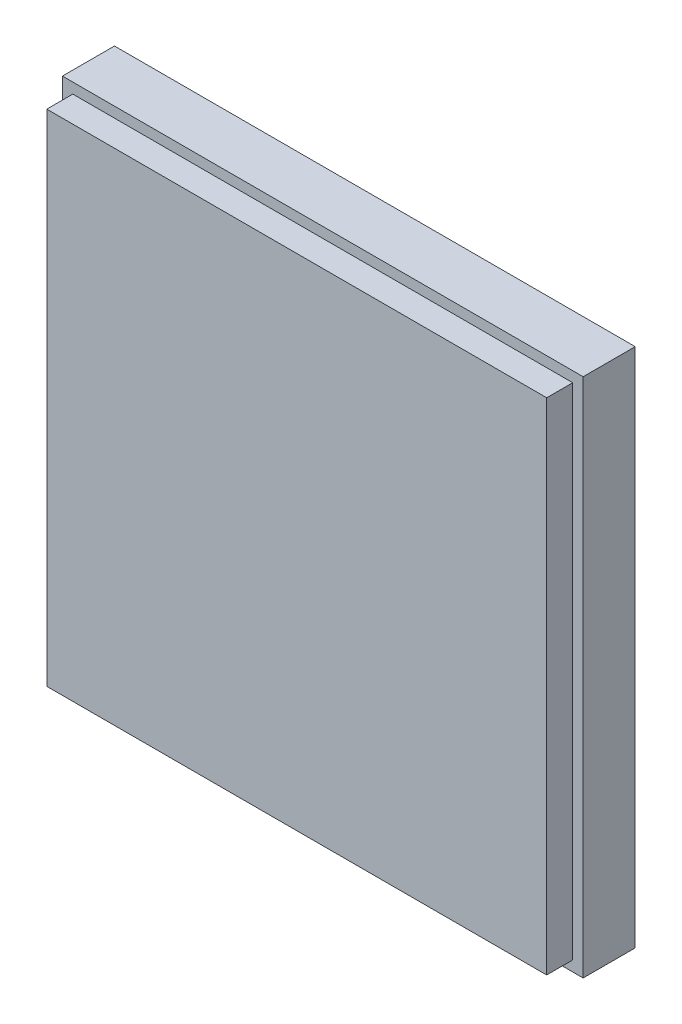
SolidWorks part; units mm, degrees
ref_plane "Front Plane" through (0, 0, 0) normal (0, 0, 1) x (1, 0, 0)
ref_plane "Top Plane" through (0, 0, 0) normal (0, 1, 0) x (1, 0, 0)
ref_plane "Right Plane" through (0, 0, 0) normal (1, 0, 0) x (0, 0, -1)
sketch "Sketch2" plane through (0, 0, 0) normal (0, 0, 1) x (1, 0, 0)
  line L1 (-53.0668, 32.2015) -> (46.9332, 32.2015)
  line L2 (-53.0668, 32.2015) -> (-53.0668, -67.7985)
  line L3 (-53.0668, -67.7985) -> (46.9332, -67.7985)
  line L4 (46.9332, 32.2015) -> (46.9332, -67.7985)
  dimension "D1" = 100
  dimension "D2" = 100
extrude "Boss-Extrude1" add sketch "Sketch2" along normal blind 10
sketch "Sketch4" plane through (0, 0, 10) normal (0, 0, 1) x (1, 0, 0)
  line L0 (46.9332, 32.2015) -> (-53.0668, 32.2015) construction
  line L1 (-51.0668, 30.2015) -> (44.9332, 30.2015)
  line L2 (-51.0668, 30.2015) -> (-51.0668, -65.7985)
  line L3 (-51.0668, -65.7985) -> (44.9332, -65.7985)
  line L4 (44.9332, 30.2015) -> (44.9332, -65.7985)
  line L5 (-53.0668, 32.2015) -> (-53.0668, -67.7985) construction
  line L6 (-53.0668, -67.7985) -> (46.9332, -67.7985) construction
  line L7 (46.9332, -67.7985) -> (46.9332, 32.2015) construction
  dimension "D1" = 2
  dimension "D2" = 2
  dimension "D3" = 2
  dimension "D4" = 2
extrude "Boss-Extrude2" add sketch "Sketch4" along normal blind 5 contours L1 L4 L3 L2
